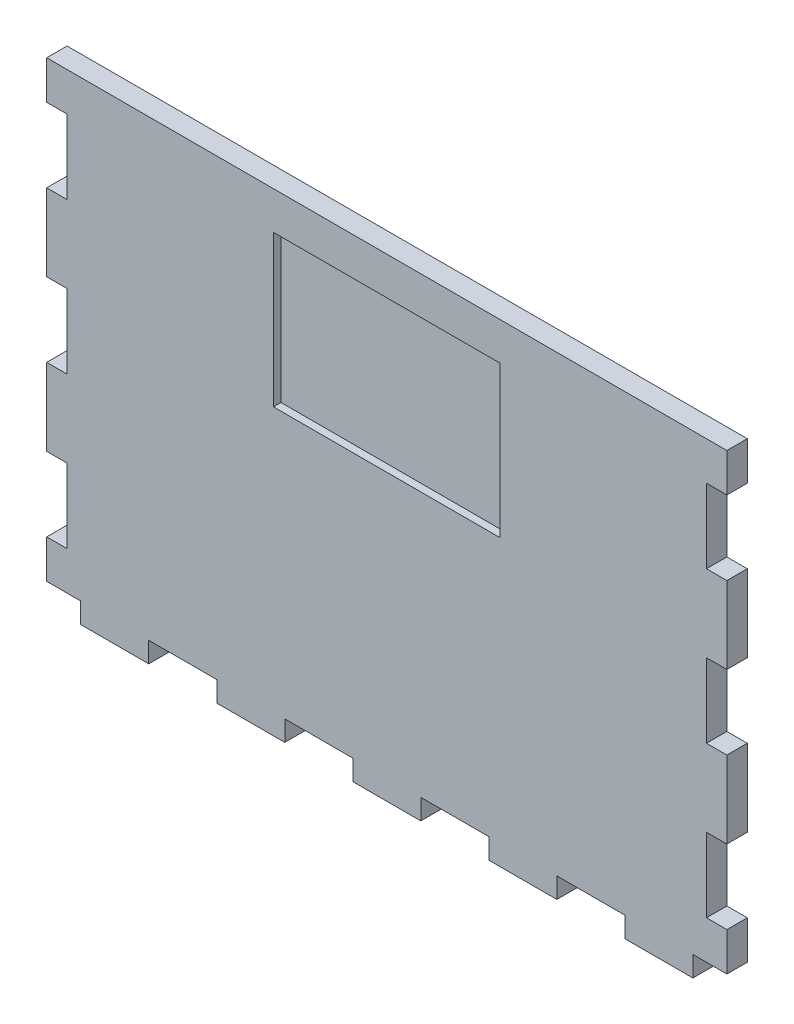
SolidWorks part; units mm, degrees
ref_plane "Plan de face" through (0, 0, 0) normal (0, 0, 1) x (1, 0, 0)
ref_plane "Plan de dessus" through (0, 0, 0) normal (0, 1, 0) x (1, 0, 0)
ref_plane "Plan de droite" through (0, 0, 0) normal (1, 0, 0) x (0, 0, -1)
sketch "Esquisse1" plane through (0, 0, 0) normal (0, 0, 1) x (1, 0, 0)
  line L1 (-45, 0) -> (45, 0)
  line L2 (-45, 0) -> (-45, -60)
  line L3 (-45, -60) -> (45, -60)
  line L4 (45, 0) -> (45, -60)
  dimension "D1" = 90
  dimension "D2" = 60
extrude "Boss.-Extru.1" add sketch "Esquisse1" along normal blind 2.7
sketch "Esquisse2" plane through (0, 0, 0) normal (0, 0, 1) x (1, 0, 0)
  line L0 (-45, -60) -> (45, -60) construction
  line L1 (-4.5, -60) -> (4.5, -60)
  line L2 (-4.5, -60) -> (-4.5, -62.7)
  line L3 (-4.5, -62.7) -> (4.5, -62.7)
  line L4 (4.5, -60) -> (4.5, -62.7)
  line L5 (0, 0) -> (0, -60) construction
  dimension "D1" = 9
  dimension "D2" = 2.7
extrude "Boss.-Extru.2" add sketch "Esquisse2" along normal blind 2.7
pattern_linear "Répétition linéaire1" count 3 spacing 18 along (1, 0, 0) count 3 spacing 18 along (-1, 0, 0) of "Boss.-Extru.2"
sketch "Esquisse3" plane through (0, 0, 0) normal (0, 0, 1) x (1, 0, 0)
  line L0 (45, -60) -> (45, 0) construction
  line L1 (45, -54.9) -> (42.3, -54.9)
  line L2 (45, -54.9) -> (45, -45.1)
  line L3 (45, -45.1) -> (42.3, -45.1)
  line L4 (42.3, -54.9) -> (42.3, -45.1)
  line L5 (42.3, -50) -> (45, -50) construction
  line L6 (40.5, -60) -> (45, -60) construction
  dimension "D1" = 10
  dimension "D2" = 9.8
  dimension "D3" = 2.7
extrude "Enlèv. mat.-Extru.1" cut sketch "Esquisse3" along normal blind 2.7
pattern_linear "Répétition linéaire2" count 5 spacing 20 along (0, 1, 0) of "Enlèv. mat.-Extru.1"
mirror "Symétrie1" about plane through (0, 0, 0) normal (1, 0, 0) of "Répétition linéaire2", "Enlèv. mat.-Extru.1"
sketch "Esquisse4" [suppressed] plane through (0, 0, 2.7) normal (0, 0, 1) x (1, 0, 0)
  line L0 (-12.5, -16) -> (12.5, -16) construction
  line L1 (-12.5, -8) -> (12.5, -8)
  line L2 (-12.5, -24) -> (12.5, -24)
  line L3 (0, 0) -> (0, -16) construction
  arc A1 (-12.5, -8) -> (-12.5, -24) centre (-12.5, -16) ccw
  arc A2 (12.5, -24) -> (12.5, -8) centre (12.5, -16) ccw
  point P2 (0, -16)
  dimension "D2" = 8
  dimension "D1" = 25
  dimension "D3" = 16
extrude "Enlèv. mat.-Extru.2" [suppressed] cut sketch "Esquisse4" against normal through all
sketch "Esquisse6" [suppressed] plane through (0, 0, 2.7) normal (0, 0, 1) x (1, 0, 0)
  line L1 (-42.3, -50) -> (42.3, -50) construction
  line L2 (42.3, -45.1) -> (42.3, -54.9) construction
  line L3 (-42.3, -45.1) -> (-42.3, -54.9) construction
  text T0 "1000" font "Arial" height in points 72
extrude "Enlèv. mat.-Extru. 1000" [suppressed] cut sketch "Esquisse6" against normal blind 1
sketch "Esquisse7" [suppressed] plane through (0, 0, 2.7) normal (0, 0, 1) x (1, 0, 0)
  line L0 (-42.3, -50) -> (42.3, -50) construction
  line L3 (42.3, -45.1) -> (42.3, -54.9) construction
  line L4 (-42.3, -45.1) -> (-42.3, -54.9) construction
  text T0 "500" font "Arial" height in points 72
extrude "Enlèv. mat.-Extru. 500" [suppressed] cut sketch "Esquisse7" against normal blind 1
sketch "Esquisse8" [suppressed] plane through (0, 0, 2.7) normal (0, 0, 1) x (1, 0, 0)
  line L0 (-42.3, -50) -> (42.3, -50) construction
  line L1 (-42.3, -45.1) -> (-42.3, -54.9) construction
  line L2 (42.3, -45.1) -> (42.3, -54.9) construction
  text T0 "100" font "Arial" height in points 72
extrude "Enlèv. mat.-Extru. 100" [suppressed] cut sketch "Esquisse8" against normal blind 1
sketch "Esquisse9" [suppressed] plane through (0, 0, 2.7) normal (0, 0, 1) x (1, 0, 0)
  line L0 (-42.3, -50) -> (42.3, -50) construction
  line L1 (-42.3, -45.1) -> (-42.3, -54.9) construction
  line L2 (42.3, -45.1) -> (42.3, -54.9) construction
  text T0 "50" font "Arial" height in points 72
extrude "Enlèv. mat.-Extru. 50" [suppressed] cut sketch "Esquisse9" against normal blind 1
sketch "Esquisse10" [suppressed] plane through (0, 0, 2.7) normal (0, 0, 1) x (1, 0, 0)
  line L0 (-42.3, -50) -> (42.3, -50) construction
  line L1 (-42.3, -45.1) -> (-42.3, -54.9) construction
  line L2 (42.3, -45.1) -> (42.3, -54.9) construction
  text T0 "25" font "Arial" height in points 72
extrude "Enlèv. mat.-Extru. 25" [suppressed] cut sketch "Esquisse10" against normal blind 1
sketch "Esquisse11" [suppressed] plane through (0, 0, 2.7) normal (0, 0, 1) x (1, 0, 0)
  line L0 (-42.3, -50) -> (42.3, -50) construction
  line L1 (-42.3, -45.1) -> (-42.3, -54.9) construction
  line L2 (42.3, -45.1) -> (42.3, -54.9) construction
  text T0 "10" font "Arial" height in points 72
extrude "Enlèv. mat.-Extru. 10" [suppressed] cut sketch "Esquisse11" against normal blind 1
sketch "Esquisse12" [suppressed] plane through (0, 0, 2.7) normal (0, 0, 1) x (1, 0, 0)
  line L0 (-42.3, -50) -> (42.3, -50) construction
  line L1 (-42.3, -45.1) -> (-42.3, -54.9) construction
  line L2 (42.3, -45.1) -> (42.3, -54.9) construction
  text T0 "5" font "Arial" height in points 72
extrude "Enlèv. mat.-Extru. 5" [suppressed] cut sketch "Esquisse12" against normal blind 1
sketch "Esquisse13" [suppressed] plane through (0, 0, 2.7) normal (0, 0, 1) x (1, 0, 0)
  line L0 (-42.3, -50) -> (42.3, -50) construction
  line L1 (-42.3, -45.1) -> (-42.3, -54.9) construction
  line L2 (42.3, -45.1) -> (42.3, -54.9) construction
  text T0 "1" font "Arial" height in points 72
extrude "Enlèv. mat.-Extru.3" [suppressed] cut sketch "Esquisse13" against normal blind 1
sketch "Esquisse14" plane through (0, 0, 2.7) normal (0, 0, 1) x (1, 0, 0)
  line L0 (0, 0) -> (0, -15) construction
  line L1 (-15, -5) -> (15, -5)
  line L2 (-15, -5) -> (-15, -25)
  line L3 (-15, -25) -> (15, -25)
  line L4 (15, -5) -> (15, -25)
  line L5 (-15, -5) -> (15, -25) construction
  line L6 (-15, -25) -> (15, -5) construction
  line L7 (45, 0) -> (-45, 0) construction
  point P0 (0, -15)
  dimension "D1" = 20
  dimension "D2" = 30
  dimension "D3" = 15
extrude "Enlèv. mat.-Extru.4" cut sketch "Esquisse14" against normal blind 1
